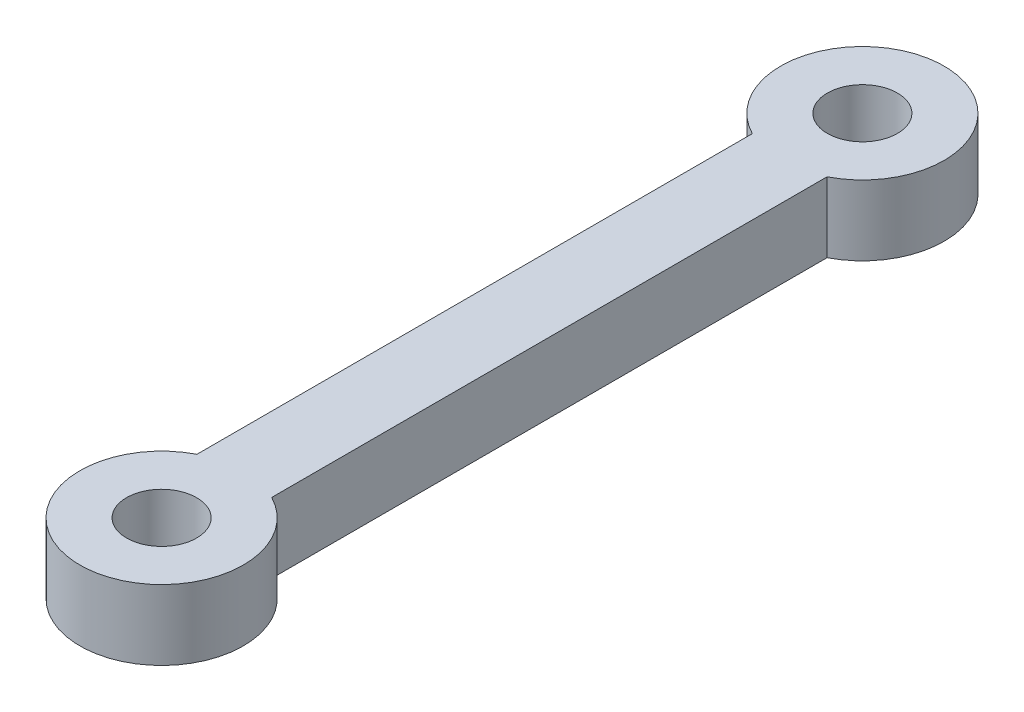
SolidWorks part; units mm, degrees
ref_plane "Front Plane" through (0, 0, 0) normal (0, 0, 1) x (1, 0, 0)
ref_plane "Top Plane" through (0, 0, 0) normal (0, 1, 0) x (1, 0, 0)
ref_plane "Right Plane" through (0, 0, 0) normal (1, 0, 0) x (0, 0, -1)
sketch "Sketch1" plane through (0, 0, 0) normal (0, 1, 0) x (1, 0, 0)
  line L0 (0, 0) -> (0, 30) construction
  line L1 (-1.6, 0) -> (-1.6, 30) construction
  line L2 (1.6, 0) -> (1.6, 30) construction
  line L3 (-1.6, 3.1129) -> (-1.6, 26.8871)
  line L4 (1.6, 26.8871) -> (1.6, 3.1129)
  line L5 (1.6, 3.1129) -> (1.2982, 3.1714)
  arc A0 (-1.6, 0) -> (1.6, 0) centre (0, 0) ccw construction
  arc A1 (1.6, 30) -> (-1.6, 30) centre (0, 30) ccw construction
  circle A2 centre (0, 0) radius 3.5 construction
  circle A3 centre (0, 0) radius 1.5
  circle A4 centre (0, 30) radius 1.5
  circle A5 centre (0, 30) radius 3.5 construction
  arc A6 (-1.6, 26.8871) -> (1.6, 26.8871) centre (0, 30) cw
  arc A7 (1.6, 3.1129) -> (-1.6, 3.1129) centre (0, 0) cw
  point P3 (0, 15)
  dimension "D3" = 7
  dimension "D1" = 3.2
  dimension "D2" = 30
extrude "Boss-Extrude1" add sketch "Sketch1" along normal blind 3
